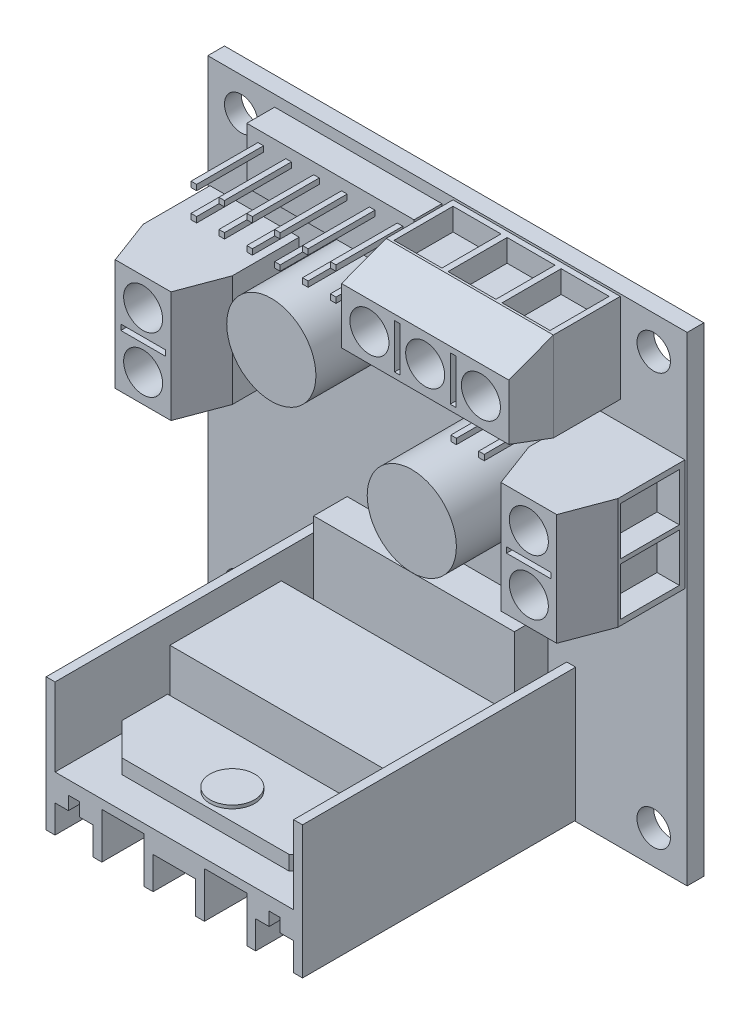
SolidWorks part; units mm, degrees
ref_plane "Front" through (0, 0, 0) normal (0, 0, 1) x (1, 0, 0)
ref_plane "Top" through (0, 0, 0) normal (0, 1, 0) x (1, 0, 0)
ref_plane "Right" through (0, 0, 0) normal (1, 0, 0) x (0, 0, -1)
sketch "草图1" plane through (0, 0, 0) normal (0, 0, 1) x (1, 0, 0)
  line L1 (0, 0) -> (43, 0)
  line L2 (0, 0) -> (0, 43)
  line L3 (0, 43) -> (43, 43)
  line L4 (43, 0) -> (43, 43)
  circle A0 centre (3, 40) radius 1.5
  circle A1 centre (40, 3) radius 1.5
  circle A2 centre (40, 40) radius 1.5
  circle A3 centre (3, 3) radius 1.5
  dimension "D3" = 3
  dimension "D4" = 3
  dimension "D5" = 3
  dimension "D6" = 3
  dimension "D1" = 43
  dimension "D2" = 43
extrude "凸台-拉伸1" add sketch "草图1" along normal blind 1.5
sketch "草图2" plane through (0, 0, 1.5) normal (0, 0, 1) x (1, 0, 0)
  line L0 (0, 0) -> (43, 0) construction
  line L2 (33, 0.1) -> (33, 12)
  line L3 (33, 12) -> (32.2, 12)
  line L4 (10, 0.1) -> (10, 12)
  line L5 (33, 0.1) -> (32.2, 0.1)
  line L6 (10.8, 12) -> (10, 12)
  line L8 (10.8, 12) -> (10.8, 5)
  line L9 (10.8, 5) -> (32.2, 5)
  line L10 (32.2, 12) -> (32.2, 5)
  line L11 (10.8, 0.1) -> (10.8, 2.6)
  line L12 (10.8, 2.6) -> (12, 2.6)
  line L13 (12, 2.6) -> (12, 3.8)
  line L14 (12, 3.8) -> (13, 3.8)
  line L15 (13, 3.8) -> (13, 2.6)
  line L16 (13, 2.6) -> (14.2, 2.6)
  line L17 (14.2, 2.6) -> (14.2, 0.1)
  line L18 (32.2, 0.1) -> (32.2, 2.6)
  line L19 (32.2, 2.6) -> (31, 2.6)
  line L20 (31, 2.6) -> (31, 3.8)
  line L21 (31, 3.8) -> (30, 3.8)
  line L22 (30, 3.8) -> (30, 2.6)
  line L23 (30, 2.6) -> (28.8, 2.6)
  line L24 (28.8, 2.6) -> (28.8, 0.1)
  line L29 (15, 0.1) -> (15, 4.2)
  line L30 (15, 4.2) -> (18.8, 4.2)
  line L31 (18.8, 0.1) -> (18.8, 4.2)
  line L33 (19.6, 0.1) -> (19.6, 3)
  line L34 (19.6, 3) -> (23.4, 3)
  line L35 (23.4, 0.1) -> (23.4, 3)
  line L37 (24.2, 0.1) -> (24.2, 4.2)
  line L38 (24.2, 4.2) -> (28, 4.2)
  line L39 (28, 0.1) -> (28, 4.2)
  line L42 (10.8, 0.1) -> (10, 0.1)
  line L43 (15, 0.1) -> (14.2, 0.1)
  line L44 (19.6, 0.1) -> (18.8, 0.1)
  line L45 (24.2, 0.1) -> (23.4, 0.1)
  line L46 (28.8, 0.1) -> (28, 0.1)
  dimension "D1" = 23
  dimension "D3" = 1
  dimension "D4" = 0.8
  dimension "D5" = 0.8
  dimension "D6" = 7
  dimension "D7" = 1.2
  dimension "D8" = 1.2
  dimension "D9" = 1.2
  dimension "D10" = 1.2
  dimension "D11" = 1.2
  dimension "D12" = 1.2
  dimension "D13" = 1.2
  dimension "D14" = 1
  dimension "D15" = 0.8
  dimension "D16" = 0.8
  dimension "D17" = 2
  dimension "D18" = 0.8
  dimension "D19" = 0.8
  dimension "D20" = 0.8
  dimension "D21" = 0.8
  dimension "D22" = 3.8
  dimension "D23" = 3.8
  dimension "D24" = 0.1
extrude "凸台-拉伸2" add sketch "草图2" along normal blind 24.5
sketch "草图3" plane through (0, 5, 0) normal (0, 1, 0) x (1, 0, 0)
  line L1 (31.9, -16) -> (11.1, -16)
  line L3 (31.9, -6) -> (11.1, -6)
  line L6 (32.2, -26) -> (10.8, -26) construction
  line L7 (31.9, -16) -> (31.9, -6)
  line L8 (11.1, -16) -> (11.1, -6)
  dimension "D1" = 10
extrude "凸台-拉伸3" add sketch "草图3" along normal blind 5
sketch "草图4" plane through (0, 5, 0) normal (0, 1, 0) x (1, 0, 0)
  line L0 (11.1, -16) -> (31.9, -16) construction
  line L1 (31.9, -16.2) -> (11.1, -16.2)
  line L2 (31.9, -16.2) -> (31.9, -20.3)
  line L3 (29, -23.2) -> (14, -23.2)
  line L4 (11.1, -16.2) -> (11.1, -20.3)
  line L5 (31.9, -20.3) -> (29, -23.2)
  line L6 (14, -23.2) -> (11.1, -20.3)
  line L7 (11.1, -6) -> (11.1, -16) construction
  dimension "D2" = 0.2
  dimension "D3" = 15
  dimension "D4" = 0
  dimension "D5" = 45
  dimension "D6" = 45
extrude "凸台-拉伸4" add sketch "草图4" along normal blind 1.3
sketch "草图5" plane through (0, 6.3, 0) normal (0, 1, 0) x (1, 0, 0)
  line L0 (14, -23.2) -> (29, -23.2) construction
  circle A0 centre (21.5, -20.8) radius 2
  dimension "D1" = 2.4
extrude "凸台-拉伸5" add sketch "草图5" along normal blind 0.3
sketch "草图6" plane through (0, 5, 0) normal (0, 1, 0) x (1, 0, 0)
  line L0 (43, -1.5) -> (0, -1.5) construction
  line L1 (30.5, -1.5) -> (12.5, -1.5)
  line L2 (30.5, -1.5) -> (30.5, -4.5)
  line L3 (30.5, -4.5) -> (12.5, -4.5)
  line L4 (12.5, -1.5) -> (12.5, -4.5)
  circle A0 centre (21.5, -20.8) radius 2 construction
  point P6 (21.5, -4.5)
  dimension "D1" = 3
  dimension "D2" = 18
  dimension "D3" = 0
extrude "凸台-拉伸6" add sketch "草图6" along normal blind 10
sketch "草图7" plane through (0, 0, 1.5) normal (0, 0, 1) x (1, 0, 0)
  line L1 (0.2, 23) -> (8.2, 23)
  line L3 (0.2, 33) -> (8.2, 33)
  line L4 (8.2, 23) -> (8.2, 33)
  line L5 (43, 43) -> (0, 43) construction
  line L6 (43, 0) -> (43, 43) construction
  line L7 (42.8, 23) -> (34.8, 23)
  line L9 (42.8, 33) -> (34.8, 33)
  line L10 (34.8, 23) -> (34.8, 33)
  line L11 (42.8, 23) -> (42.8, 33)
  line L13 (37, 42.8) -> (37, 34.8)
  line L14 (37, 34.8) -> (22, 34.8)
  line L15 (22, 42.8) -> (22, 34.8)
  line L16 (0.2, 23) -> (0.2, 33)
  line L17 (37, 42.8) -> (22, 42.8)
  dimension "D2" = 10
  dimension "D3" = 10
  dimension "D5" = 15
  dimension "D6" = 6
extrude "凸台-拉伸7" add sketch "草图7" along normal blind 6
sketch "草图8" plane through (0, 33, 0) normal (0, 1, 0) x (1, 0, 0)
  line L0 (42.8, -7.5) -> (34.8, -7.5)
  line L1 (34.8, -7.5) -> (36.3, -11.5)
  line L2 (36.3, -11.5) -> (41.3, -11.5)
  line L3 (41.3, -11.5) -> (42.8, -7.5)
  dimension "D1" = 4
  dimension "D2" = 5
  dimension "D3" = 1.5
extrude "凸台-拉伸8" add sketch "草图8" against normal blind 10
sketch "草图9" plane through (0, 33, 0) normal (0, 1, 0) x (1, 0, 0)
  line L0 (8.2, -7.5) -> (6.7, -11.5)
  line L1 (6.7, -11.5) -> (1.7, -11.5)
  line L2 (1.7, -11.5) -> (0.2, -7.5)
  line L3 (0.2, -7.5) -> (8.2, -7.5)
  dimension "D1" = 5
  dimension "D2" = 4
  dimension "D3" = 1.5
extrude "凸台-拉伸9" add sketch "草图9" against normal blind 10
sketch "草图10" plane through (37, 0, 0) normal (1, 0, 0) x (0, 0, -1)
  line L0 (-7.5, 34.8) -> (-7.5, 42.8)
  line L1 (-7.5, 42.8) -> (-11.5, 41.3)
  line L2 (-11.5, 41.3) -> (-11.5, 36.3)
  line L3 (-11.5, 36.3) -> (-7.5, 34.8)
  dimension "D1" = 5
  dimension "D2" = 4
  dimension "D3" = 1.5
extrude "凸台-拉伸10" add sketch "草图10" against normal blind 15 separate body
sketch "草图11" plane through (0, 0, 11.5) normal (0, 0, 1) x (1, 0, 0)
  line L0 (36.3, 23) -> (41.3, 23) construction
  line L1 (42.8, 33) -> (34.8, 33) construction
  line L2 (41.3, 23) -> (41.3, 33) construction
  line L3 (40.8, 27.75) -> (36.8, 27.75)
  line L4 (40.8, 27.75) -> (40.8, 28.25)
  line L5 (40.8, 28.25) -> (36.8, 28.25)
  line L6 (36.8, 27.75) -> (36.8, 28.25)
  line L7 (1.7, 23) -> (6.7, 23) construction
  line L8 (6.7, 23) -> (6.7, 33) construction
  line L9 (6.2, 27.75) -> (2.2, 27.75)
  line L10 (6.2, 27.75) -> (6.2, 28.25)
  line L11 (6.2, 28.25) -> (2.2, 28.25)
  line L12 (2.2, 27.75) -> (2.2, 28.25)
  line L13 (37, 34.8) -> (37, 42.8) construction
  line L14 (22, 41.3) -> (22, 36.3) construction
  line L15 (37, 41.3) -> (37, 36.3) construction
  line L16 (32.25, 36.8) -> (31.75, 36.8)
  line L17 (32.25, 36.8) -> (32.25, 40.8)
  line L18 (32.25, 40.8) -> (31.75, 40.8)
  line L19 (31.75, 36.8) -> (31.75, 40.8)
  line L21 (27.25, 36.8) -> (26.75, 36.8)
  line L22 (27.25, 36.8) -> (27.25, 40.8)
  line L23 (27.25, 40.8) -> (26.75, 40.8)
  line L24 (26.75, 36.8) -> (26.75, 40.8)
  circle A0 centre (38.8, 25.5) radius 1.75
  circle A1 centre (38.8, 30.5) radius 1.75
  circle A2 centre (4.2, 25.5) radius 1.75
  circle A3 centre (4.2, 30.5) radius 1.75
  circle A4 centre (34.5, 38.8) radius 1.75
  circle A5 centre (24.5, 38.8) radius 1.75
  circle A6 centre (29.5, 38.8) radius 1.75
  point P14 (40.8, 28)
  point P15 (41.3, 28)
  point P42 (32.25, 38.8)
  point P45 (37, 38.8)
  dimension "D1" = 2.5
  dimension "D2" = 2.5
  dimension "D7" = 2.5
  dimension "D10" = 2.5
  dimension "D11" = 2.5
  dimension "D12" = 4
  dimension "D15" = 0
  dimension "D3" = 0.5
  dimension "D4" = 0.5
  dimension "D5" = 4
  dimension "D6" = 0
  dimension "D8" = 4
  dimension "D9" = 0.5
  dimension "D13" = 0.5
  dimension "D14" = 0
  dimension "D16" = 0.5
  dimension "D17" = 4.75
  dimension "D18" = 4.75
extrude "切除-拉伸1" cut sketch "草图11" against normal blind 4
sketch "草图12" plane through (42.8, 0, 0) normal (1, 0, 0) x (0, 0, -1)
  line L0 (-7.5, 23) -> (-7.5, 33) construction
  line L1 (-7.3, 23.5) -> (-2, 23.5)
  line L2 (-7.3, 23.5) -> (-7.3, 27.8)
  line L3 (-7.3, 27.8) -> (-2, 27.8)
  line L4 (-2, 23.5) -> (-2, 27.8)
  line L5 (-7.5, 23) -> (-1.5, 23) construction
  line L6 (-1.5, 23) -> (-1.5, 33) construction
  line L7 (-7.5, 33) -> (-1.5, 33) construction
  line L8 (-7.3, 28.2) -> (-2, 28.2)
  line L9 (-7.3, 28.2) -> (-7.3, 32.5)
  line L10 (-7.3, 32.5) -> (-2, 32.5)
  line L11 (-2, 28.2) -> (-2, 32.5)
  dimension "D1" = 0.2
  dimension "D2" = 0.5
  dimension "D3" = 0.5
  dimension "D4" = 0.5
  dimension "D5" = 4.3
  dimension "D6" = 4.3
extrude "切除-拉伸2" cut sketch "草图12" against normal blind 2
sketch "草图13" plane through (0, 42.8, 0) normal (0, 1, 0) x (1, 0, 0)
  line L0 (43, -1.5) -> (0, -1.5) construction
  line L1 (36.5, -7.3) -> (32.2, -7.3)
  line L2 (36.5, -7.3) -> (36.5, -2)
  line L3 (36.5, -2) -> (32.2, -2)
  line L4 (32.2, -7.3) -> (32.2, -2)
  line L5 (37, -7.5) -> (22, -7.5) construction
  line L6 (37, -7.5) -> (37, -1.5) construction
  line L7 (22, -7.5) -> (22, -1.5) construction
  line L8 (31.65, -7.3) -> (27.35, -7.3)
  line L9 (31.65, -7.3) -> (31.65, -2)
  line L10 (31.65, -2) -> (27.35, -2)
  line L11 (27.35, -7.3) -> (27.35, -2)
  line L12 (26.8, -7.3) -> (22.5, -7.3)
  line L13 (26.8, -7.3) -> (26.8, -2)
  line L14 (26.8, -2) -> (22.5, -2)
  line L15 (22.5, -7.3) -> (22.5, -2)
  dimension "D1" = 4.3
  dimension "D2" = 0.5
  dimension "D3" = 0.2
  dimension "D4" = 0.5
  dimension "D5" = 0.5
  dimension "D6" = 4.3
  dimension "D7" = 4.3
  dimension "D8" = 0.55
extrude "切除-拉伸3" cut sketch "草图13" against normal blind 2
sketch "草图14" plane through (0.2, 0, 0) normal (-1, 0, 0) x (0, 0, 1)
  line L0 (7.5, 33) -> (1.5, 33) construction
  line L1 (7.3, 32.5) -> (2, 32.5)
  line L2 (7.3, 32.5) -> (7.3, 28.2)
  line L3 (7.3, 28.2) -> (2, 28.2)
  line L4 (2, 32.5) -> (2, 28.2)
  line L5 (1.5, 43) -> (1.5, 0) construction
  line L6 (7.5, 33) -> (7.5, 23) construction
  line L7 (7.5, 23) -> (1.5, 23) construction
  line L8 (7.3, 27.8) -> (2, 27.8)
  line L9 (7.3, 27.8) -> (7.3, 23.5)
  line L10 (7.3, 23.5) -> (2, 23.5)
  line L11 (2, 27.8) -> (2, 23.5)
  dimension "D1" = 0.5
  dimension "D2" = 0.5
  dimension "D3" = 0.2
  dimension "D4" = 4.3
  dimension "D5" = 0.5
  dimension "D6" = 4.3
extrude "切除-拉伸4" cut sketch "草图14" against normal blind 2
sketch "草图15" plane through (0, 0, 1.5) normal (0, 0, 1) x (1, 0, 0)
  line L1 (36.3, 23) -> (36.3, 33) construction
  line L2 (36.3, 23) -> (41.3, 23) construction
  line L3 (1.7, 33) -> (6.7, 33) construction
  line L4 (6.7, 23) -> (6.7, 33) construction
  circle A0 centre (27.3, 25) radius 4
  circle A1 centre (14.7, 32) radius 4
  dimension "D1" = 9
  dimension "D2" = 2
  dimension "D3" = 1
  dimension "D4" = 8
extrude "凸台-拉伸11" add sketch "草图15" along normal blind 9
sketch "草图16" plane through (0, 0, 1.5) normal (0, 0, 1) x (1, 0, 0)
  line L0 (22, 42.8) -> (22, 34.8) construction
  line L1 (21, 37) -> (6, 37)
  line L2 (21, 37) -> (21, 42)
  line L3 (21, 42) -> (6, 42)
  line L4 (6, 37) -> (6, 42)
  line L5 (43, 43) -> (0, 43) construction
  line L6 (34.8, 33) -> (34.8, 23) construction
  line L7 (34.3, 31.878) -> (29.3, 31.878)
  line L8 (34.3, 31.878) -> (34.3, 33.478)
  line L9 (34.3, 33.478) -> (29.3, 33.478)
  line L10 (29.3, 31.878) -> (29.3, 33.478)
  point P12 (34.3, 32.678)
  dimension "D1" = 15
  dimension "D2" = 5
  dimension "D3" = 1
  dimension "D4" = 1
  dimension "D5" = 5
  dimension "D6" = 1.6
  dimension "D7" = 0.5
extrude "凸台-拉伸12" add sketch "草图16" along normal blind 2.5
sketch "草图17" plane through (0, 0, 4) normal (0, 0, 1) x (1, 0, 0)
  line L0 (34.3, 31.878) -> (34.3, 33.478) construction
  line L1 (33.3, 32.428) -> (32.8, 32.428)
  line L2 (33.3, 32.428) -> (33.3, 32.928)
  line L3 (33.3, 32.928) -> (32.8, 32.928)
  line L4 (32.8, 32.428) -> (32.8, 32.928)
  line L5 (30.8, 32.428) -> (30.3, 32.428)
  line L6 (30.8, 32.428) -> (30.8, 32.928)
  line L7 (30.8, 32.928) -> (30.3, 32.928)
  line L8 (30.3, 32.428) -> (30.3, 32.928)
  line L9 (29.3, 33.478) -> (29.3, 31.878) construction
  line L10 (34.3, 33.478) -> (29.3, 33.478) construction
  dimension "D1" = 0.5
  dimension "D2" = 0.5
  dimension "D3" = 0.5
  dimension "D4" = 0.5
  dimension "D5" = 1
  dimension "D6" = 1
  dimension "D7" = 0.55
  dimension "D8" = 0.55
extrude "凸台-拉伸13" add sketch "草图17" along normal blind 6
sketch "草图18" plane through (0, 0, 4) normal (0, 0, 1) x (1, 0, 0)
  line L0 (6, 37) -> (21, 37) construction
  line L1 (20, 38) -> (19.5, 38)
  line L2 (20, 38) -> (20, 38.5)
  line L3 (20, 38.5) -> (19.5, 38.5)
  line L4 (19.5, 38) -> (19.5, 38.5)
  line L5 (21, 37) -> (21, 42) construction
  line L6 (21, 42) -> (6, 42) construction
  line L7 (20, 40.5) -> (19.5, 40.5)
  line L8 (20, 40.5) -> (20, 41)
  line L9 (20, 41) -> (19.5, 41)
  line L10 (19.5, 40.5) -> (19.5, 41)
  dimension "D1" = 0.5
  dimension "D2" = 0.5
  dimension "D3" = 1
  dimension "D4" = 1
  dimension "D5" = 0.5
  dimension "D6" = 1
extrude "凸台-拉伸14" add sketch "草图18" along normal blind 6
pattern_linear "阵列(线性)1" count 6 spacing 2.5 along (-1, 0, 0) of "凸台-拉伸14"
sketch "草图19" plane through (0, 0, 0) normal (0, 0, -1) x (-1, 0, 0)
  circle A0 centre (-13.8834, 11.3719) radius 0.25
  circle A1 centre (-13.8834, 16.6418) radius 0.25
extrude "凸台-拉伸15" add sketch "草图19" along normal blind 2.2
pattern_linear "阵列(线性)2" count 9 spacing 2 along (1, 0, 0) of "凸台-拉伸15"
equation "\"12、\"=15.4067"
